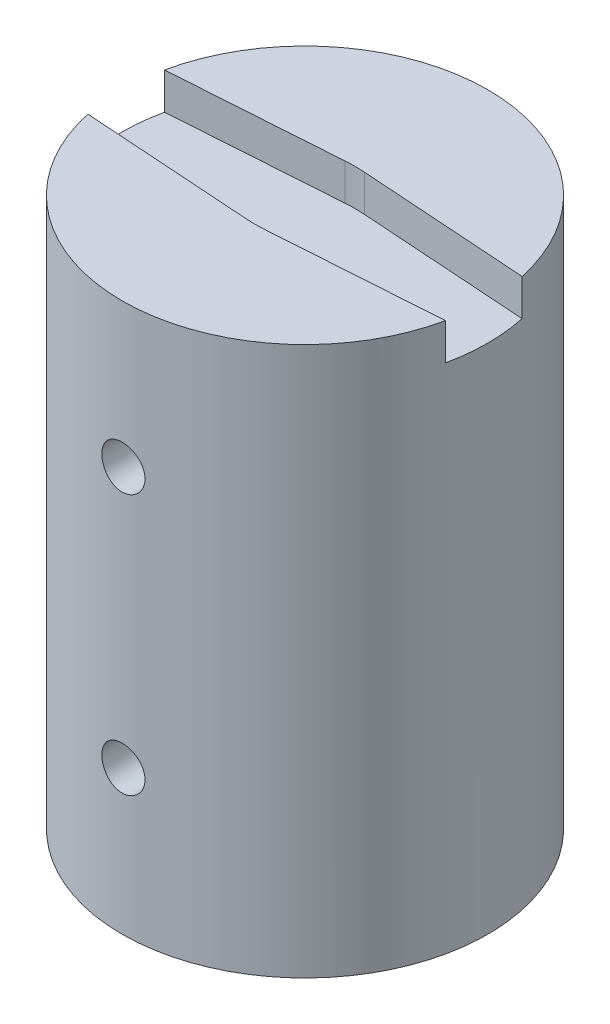
SolidWorks part; units mm, degrees
material "ABS"
ref_plane "Front Plane" through (0, 0, 0) normal (0, 0, 1) x (1, 0, 0)
ref_plane "Top Plane" through (0, 0, 0) normal (0, 1, 0) x (1, 0, 0)
ref_plane "Right Plane" through (0, 0, 0) normal (1, 0, 0) x (0, 0, -1)
sketch "Sketch1" plane through (0, 0, 0) normal (0, 1, 0) x (1, 0, 0)
  circle A0 centre (0, 0) radius 10.16
  circle A1 centre (0, 0) radius 12.7
  dimension "D1" = 20.32
  dimension "D2" = 25.4
extrude "Boss-Extrude1" add sketch "Sketch1" along normal blind 38.1
sketch "Sketch2" plane through (0, 38.1, 0) normal (0, 1, 0) x (1, 0, 0)
  circle A0 centre (0, 0) radius 12.7
extrude "Boss-Extrude2" add sketch "Sketch2" against normal blind 5.08
sketch "Sketch3" plane through (0, 38.1, 0) normal (0, 1, 0) x (1, 0, 0)
  line L4 (-14.75, 0) -> (14.75, 0)
  line L5 (0, -3.5) -> (0, 3.5)
  line L6 (0, 3.5) -> (14.75, 2.5)
  line L7 (0, 3.5) -> (-14.75, 2.5)
  line L8 (0, -3.5) -> (-14.75, -2.5)
  line L9 (0, -3.5) -> (14.75, -2.5)
  circle A0 centre (14.75, 0) radius 2.5
  circle A1 centre (-14.75, 0) radius 2.5
  point P13 (0, 0)
  dimension "D2" = 3.5
  dimension "D1" = 14.75
extrude "Cut-Extrude1" cut sketch "Sketch3" against normal blind 2.54
fillet "Fillet1" radius 10 2 edges at (0, 36.83, 3.5) (0, 36.83, -3.5)
ref_plane "Plane1" through (0, 0, -12.7) normal (0, 0, 1) x (1, 0, 0)
sketch "Sketch5" plane through (0, 0, -12.7) normal (0, 0, 1) x (1, 0, 0)
  line L0 (12.4187, 38.1) -> (-12.4187, 38.1) construction
  line L1 (-12.7, 0) -> (12.7, 0) construction
  circle A0 centre (0, 28.1) radius 1.5
  circle A1 centre (0, 10) radius 1.5
  dimension "D1" = 3
  dimension "D2" = 10
  dimension "D3" = 10
extrude "Cut-Extrude2" cut sketch "Sketch5" along normal through all and the other way through all
